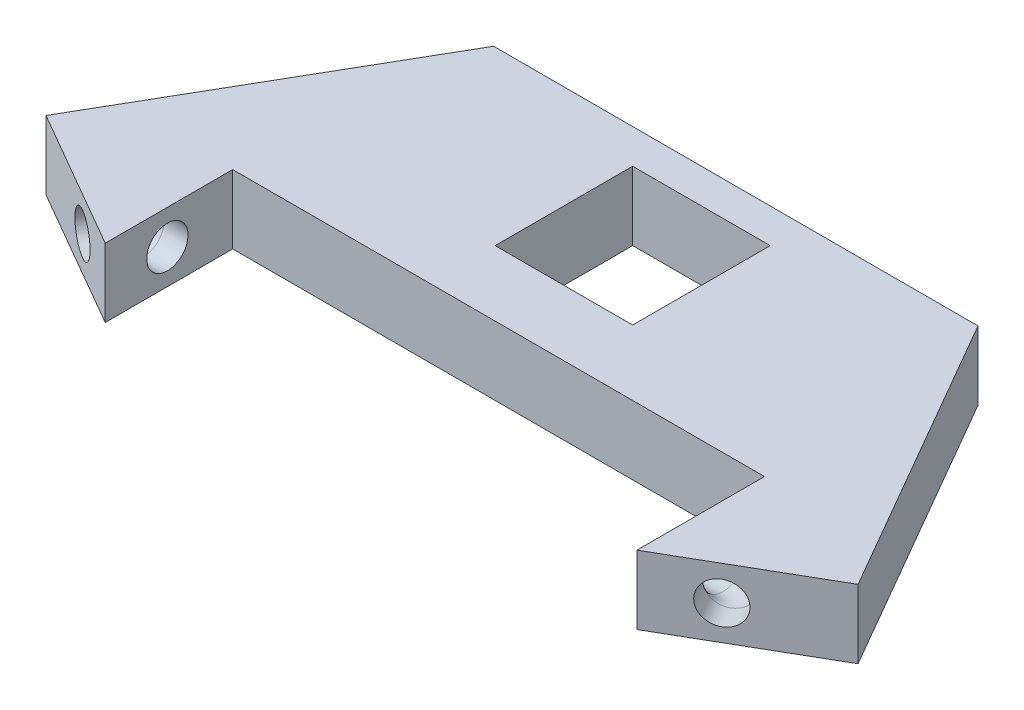
SolidWorks part; units mm, degrees
material "Custom Plastic"
ref_plane "Front Plane" through (0, 0, 0) normal (0, 0, 1) x (1, 0, 0)
ref_plane "Top Plane" through (0, 0, 0) normal (0, 1, 0) x (1, 0, 0)
ref_plane "Right Plane" through (0, 0, 0) normal (1, 0, 0) x (0, 0, -1)
sketch "Sketch1" plane through (0, 0, 0) normal (0, 1, 0) x (1, 0, 0)
  line L0 (-36.6617, 63.5) -> (-36.6617, 83.5) construction
  line L1 (-36.6617, 63.5) -> (-73.3235, 0) construction
  line L2 (-73.3235, 0) -> (-36.6617, -63.5) construction
  line L3 (-36.6617, -63.5) -> (36.6617, -63.5) construction
  line L4 (36.6617, -63.5) -> (73.3235, 0) construction
  line L5 (73.3235, 0) -> (36.6617, 63.5) construction
  line L6 (36.6617, 63.5) -> (-36.6617, 63.5) construction
  line L7 (-36.6617, 83.5) -> (36.6617, 83.5) construction
  line L8 (36.6617, 83.5) -> (36.6617, 63.5) construction
  line L9 (36.6617, 63.5) -> (53.9823, 73.5) construction
  line L10 (53.9823, 73.5) -> (90.644, 10) construction
  line L11 (90.644, 10) -> (73.3235, 0) construction
  line L12 (73.3235, 0) -> (90.644, -10) construction
  line L13 (90.644, -10) -> (53.9823, -73.5) construction
  line L14 (53.9823, -73.5) -> (36.6617, -63.5) construction
  line L15 (36.6617, -63.5) -> (36.6617, -83.5) construction
  line L16 (36.6617, -83.5) -> (-36.6617, -83.5) construction
  line L17 (-36.6617, -83.5) -> (-36.6617, -63.5) construction
  line L18 (-36.6617, -63.5) -> (-53.9823, -73.5) construction
  line L19 (-53.9823, -73.5) -> (-90.644, -10) construction
  line L20 (-90.644, -10) -> (-73.3235, 0) construction
  line L21 (-73.3235, 0) -> (-90.644, 10) construction
  line L22 (-90.644, 10) -> (-53.9823, 73.5) construction
  line L23 (-53.9823, 73.5) -> (-36.6617, 63.5) construction
  line L24 (-93.376, 9.2679) -> (-54.7143, 76.2321)
  line L25 (-54.7143, 76.2321) -> (-38.6617, 66.9641)
  line L26 (-38.6617, 66.9641) -> (-38.6617, 85.5)
  line L27 (-38.6617, 85.5) -> (38.6617, 85.5)
  line L28 (38.6617, 85.5) -> (38.6617, 66.9641)
  line L29 (38.6617, 66.9641) -> (54.7143, 76.2321)
  line L30 (54.7143, 76.2321) -> (93.376, 9.2679)
  line L31 (93.376, 9.2679) -> (77.3235, 0)
  line L32 (77.3235, 0) -> (93.376, -9.2679)
  line L33 (93.376, -9.2679) -> (54.7143, -76.2321)
  line L34 (54.7143, -76.2321) -> (38.6617, -66.9641)
  line L35 (38.6617, -66.9641) -> (38.6617, -85.5)
  line L36 (38.6617, -85.5) -> (-38.6617, -85.5)
  line L37 (-38.6617, -85.5) -> (-38.6617, -66.9641)
  line L38 (-38.6617, -66.9641) -> (-54.7143, -76.2321)
  line L39 (-54.7143, -76.2321) -> (-93.376, -9.2679)
  line L40 (-93.376, -9.2679) -> (-77.3235, 0)
  line L41 (-77.3235, 0) -> (-93.376, 9.2679)
  line L42 (87.2724, -38.8397) -> (77.2724, -56.1603)
  line L43 (-10, 95) -> (10, 95)
  line L44 (-10, 95) -> (-10, 115)
  line L45 (-10, 115) -> (10, 115)
  line L46 (10, 95) -> (10, 115)
  line L55 (87.2724, -38.8397) -> (104.5929, -48.8397)
  line L56 (104.5929, -48.8397) -> (94.5929, -66.1603)
  line L57 (77.2724, -56.1603) -> (94.5929, -66.1603)
  line L58 (-77.2724, -56.1603) -> (-87.2724, -38.8397)
  line L59 (-77.2724, -56.1603) -> (-94.5929, -66.1603)
  line L60 (-94.5929, -66.1603) -> (-104.5929, -48.8397)
  line L61 (-87.2724, -38.8397) -> (-104.5929, -48.8397)
  line L62 (-35.2184, 120) -> (35.2184, 120)
  line L63 (35.2184, 120) -> (121.5322, -29.5)
  line L64 (121.5322, -29.5) -> (86.3139, -90.5)
  line L65 (86.3139, -90.5) -> (-86.3139, -90.5)
  line L66 (-86.3139, -90.5) -> (-121.5322, -29.5)
  line L67 (-121.5322, -29.5) -> (-35.2184, 120)
  line L68 (-54.7143, 76.2321) -> (-59.0444, 78.7321)
  line L69 (54.7143, 76.2321) -> (59.0444, 78.7321)
  circle A0 centre (0, 0) radius 63.5 construction
  circle A2 centre (0, 0) radius 95 construction
  point P1 (0, 63.5)
  point P49 (0, 95)
  point P51 (-82.2724, -47.5)
  point P60 (82.2724, -47.5)
  point P67 (0, 115)
  dimension "D1" = 127
  dimension "D8" = 190
  dimension "D3" = 20
  dimension "D6" = 20
  dimension "D7" = 20
  dimension "D10" = 5
  dimension "D11" = 5
  dimension "D12" = 5
  dimension "D13" = 5
  dimension "D14" = 5
  dimension "D15" = 5
  dimension "D5" = 2
  dimension "D4" = 6
  dimension "D9" = 3
extrude "Boss-Extrude1" add sketch "Sketch1" along normal blind 10 contours L29 L69 L63 L62 L67 L68 L25 L26 L27 L28 L46 L43 L44 L45
ref_plane "Plane2" through (0, 5, 0) normal (0, 1, 0) x (1, 0, 0)
sketch "Sketch2" plane through (-38.6617, 0, 0) normal (1, 0, 0) x (0, 0, -1)
  line L0 (66.9641, 10) -> (66.9641, 0) construction
  line L2 (85.5, 10) -> (85.5, 0) construction
  circle A1 centre (76, 5) radius 3
  point P5 (66.9641, 5)
  point P7 (76.3573, 5)
  dimension "D1" = 9.5
  dimension "D2" = 6
sketch "Sketch3" plane through (0, 5, 0) normal (0, 1, 0) x (1, 0, 0)
  line L0 (-38.6617, 76) -> (-42.1466, 76)
  line L1 (-38.6617, 73) -> (-38.6617, 79) construction
  line L2 (-44.7446, 74.5) -> (-46.4871, 71.4821)
  line L3 (-38.6617, 66.9641) -> (-59.0444, 78.7321) construction
  arc A0 (-42.1466, 76) -> (-44.7446, 74.5) centre (-42.1466, 73) ccw
  dimension "D1" = 3
sweep "Cut-Sweep1" cut profiles "Sketch2" path "Sketch3"
mirror "Mirror3" about plane through (0, 0, 0) normal (1, 0, 0) of "Cut-Sweep1"
